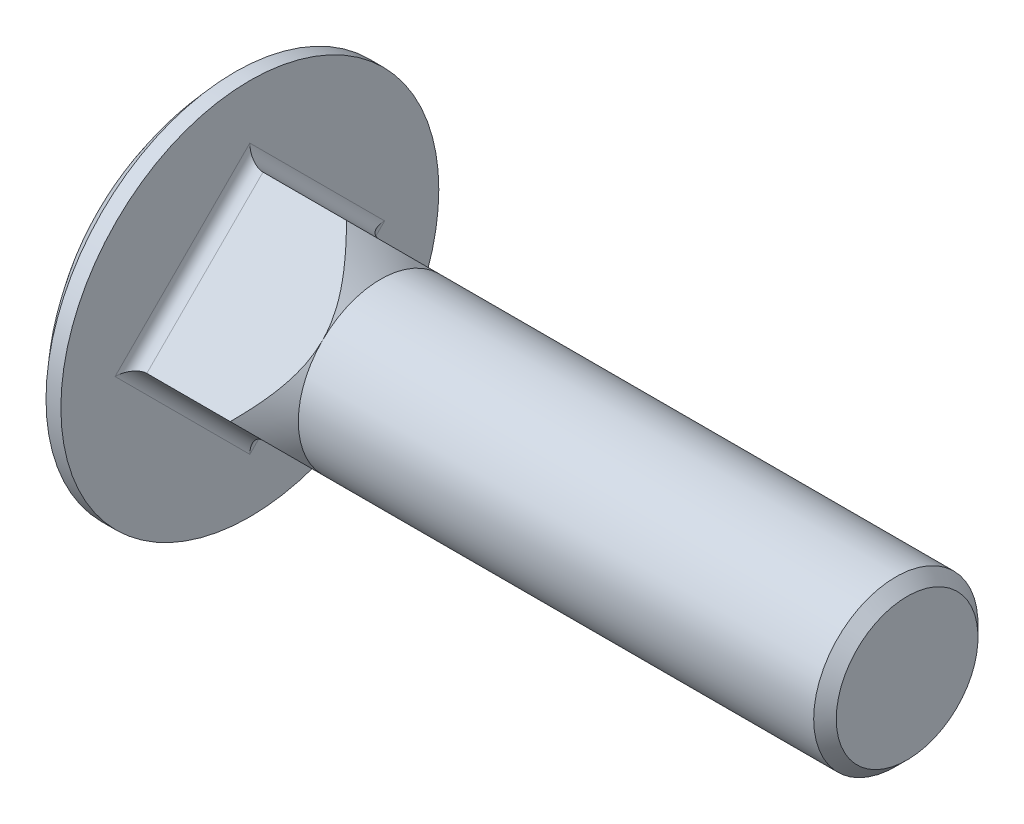
SolidWorks part; units mm, degrees
revolve "Base-Revolve" add sketch "BodySke" angle 360 about L6
sketch "BodySke" plane through (0, 0, 0) normal (0, 0, 1) x (1, 0, 0)
  line L1 (9.0906, 23) -> (10.9, 23)
  line L2 (10.9, 23) -> (10.9, 10)
  line L3 (10.9, 10) -> (89.526, 10)
  line L4 (90.9, 8.626) -> (90.9, 0)
  line L5 (90.9, 0) -> (0, 0)
  line L6 (-31.75, 0) -> (127, 0) construction
  line L8 (90.9, 8.626) -> (89.526, 10)
  line L10 (90.9, -8.626) -> (89.526, -10) construction
  line L11 (13.4, 7.799) -> (13.4, 1.449) construction
  line L12 (30.9, 7.799) -> (30.9, 1.449) construction
  line L13 (30.9, 7.799) -> (30.9, 1.449) construction
  arc A0 (9.0906, 23) -> (0, 0) centre (33.6413, 0) ccw
  dimension "Length" = 80
  dimension "Body_ch_ang" = 45
  dimension "Diameter" = 20
  dimension "Minor_dia" = 17.252
  dimension "Advance" = 2.5
  dimension "Thread_nom" = 60
  dimension "Thread_length" = 60
  dimension "Head_dia" = 46
  dimension "Head_ht" = 10.9
  dimension "D1" = 1.8094
cosmetic thread "ThreadCosmetic" [suppressed] parameters "Thread_length"=60, "Thread_minor"=17.252
ref_plane "Plane1" through (0, 0, 0) normal (0, 0, 1) x (1, 0, 0)
ref_plane "Plane2" through (0, 0, 0) normal (0, 1, 0) x (1, 0, 0)
ref_plane "Plane3" through (0, 0, 0) normal (1, 0, 0) x (0, 0, -1)
sketch "Sketch1" plane through (10.9, 0, 0) normal (1, 0, 0) x (0, 0, -1)
  line L0 (0, 14.1421) -> (14.1421, 0)
  line L1 (14.1421, 0) -> (0, -14.1421)
  line L2 (0, -14.1421) -> (-14.1421, 0)
  line L3 (-14.1421, 0) -> (0, 14.1421)
  circle A0 centre (0, 0) radius 10 construction
  circle A1 centre (0, 0) radius 23 construction
  dimension "D1" = 20
extrude "Boss-Extrude1" add sketch "Sketch1" along normal blind 15.9
sketch "Sketch2" plane through (0, 0, 0) normal (0, 0, 1) x (1, 0, 0)
  line L0 (0, 0) -> (101.6, 0) construction
  line L1 (26.8, 10) -> (31.8, 10)
  line L2 (26.8, 10) -> (12.8, 24)
  line L3 (31.8, 10) -> (31.8, 24)
  line L4 (31.8, 24) -> (12.8, 24)
  dimension "D1" = 20
  dimension "D2" = 26.8
  dimension "D3" = 48
  dimension "D4" = 5
  dimension "D5" = 45
revolve "Cut-Revolve1" cut sketch "Sketch2" angle 360 about L0
fillet "Fillet1" radius 1.6 4 edges at (10.9, 7.0711, -7.0711) (10.9, -7.0711, -7.0711) (10.9, 7.0711, 7.0711) (10.9, -7.0711, 7.0711)
sketch "ThdSchSke" plane through (0, 0, 0) normal (0, 0, 1) x (1, 0, 0)
  line L0 (30.9, -8.626) -> (29.9379, -10)
  line L1 (30.9, -8.626) -> (31.8621, -10)
  line L2 (31.8621, -10) -> (31.8621, -12.5)
  line L3 (0, 0) -> (5.1513, 0) construction
  line L5 (31.8621, -12.5) -> (29.9379, -12.5)
  line L6 (29.9379, -12.5) -> (29.9379, -10)
  arc A0 (9.0906, 23) -> (9.0906, -23) centre (33.6413, 0) ccw construction
  dimension "Thread_minor" = 17.252
  dimension "Diameter" = 20
  dimension "Start" = 30.9
revolve "ThreadSchematic" [suppressed] cut sketch "ThdSchSke" angle 360 about L3
pattern_linear "ThdSchPat" [suppressed]
equation "\"Thread_minor@ThreadCosmetic\"  =  \"Minor_dia@BodySke\""
equation "\"Thread_length@ThreadCosmetic\" = ((sgn( (\"Length@BodySke\" - \"Advance@BodySke\" * 3.0) - \"Thread_nom@BodySke\" )-1)*( (\"Length@BodySke\" - \"Advance@BodySke\" * 3.0) - \"Thread_nom@BodySke\" ))/-2+ \"Thread_nom@BodySke\""
equation "\"Thread_minor@ThdSchSke\" = \"Minor_dia@BodySke\""
equation "\"Diameter@ThdSchSke\" = \"Diameter@BodySke\""
equation "\"Overcut@ThdSchSke\" = \"Diameter@BodySke\" * 1.25"
equation "\"Start@ThdSchSke\" = \"Head_ht@BodySke\" + \"Length@BodySke\" - \"Thread_length@ThreadCosmetic\"  '---Non-countersunk---"
equation "\"Num_threads@ThdSchPat\" = int( \"Thread_length@ThreadCosmetic\" / \"Advance@BodySke\" + 0.999 )  + 1"
equation "\"Advance@ThdSchPat\" = \"Thread_length@ThreadCosmetic\" /  (\"Num_threads@ThdSchPat\" - 1) 'relax it"
equation "\"Num_threads@ThdSchPat\" = \"Num_threads@ThdSchPat\" - sgn( \"Num_threads@ThdSchPat\" - 1) '---chamfered tips only---"
equation "\"D1@BodySke\" = \"Head_ht@BodySke\" * .166"
equation "\"D1@Sketch2\" = \"Diameter@BodySke\""
equation "\"D2@Sketch2\" = \"Head_ht@BodySke\" + \"NeckHt@Boss-Extrude1\""
equation "\"D3@Sketch2\" = \"Head_dia@BodySke\" + 2"
equation "\"D1@Sketch1\" = \"Diameter@BodySke\""
